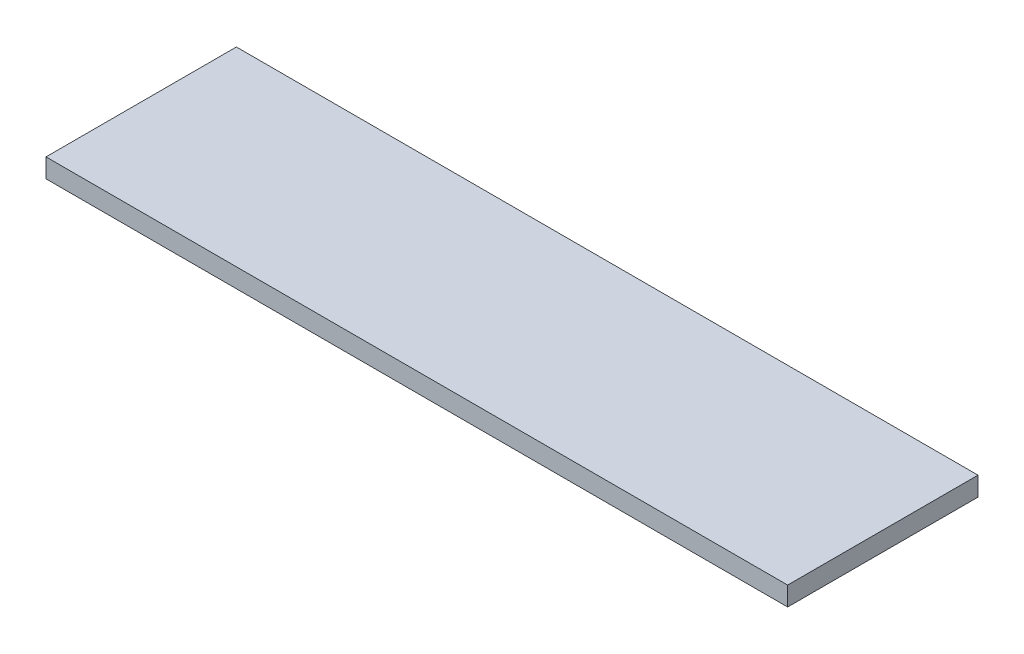
SolidWorks part; units mm, degrees
ref_plane "Front Plane" through (0, 0, 0) normal (0, 0, 1) x (1, 0, 0)
ref_plane "Top Plane" through (0, 0, 0) normal (0, 1, 0) x (1, 0, 0)
ref_plane "Right Plane" through (0, 0, 0) normal (1, 0, 0) x (0, 0, -1)
sketch "Sketch1" plane through (0, 0, 0) normal (0, 1, 0) x (1, 0, 0)
  line L0 (-47.625, 0) -> (47.625, 0) construction
  line L1 (-47.625, 7.9375) -> (47.625, 7.9375)
  line L2 (-47.625, -7.9375) -> (47.625, -7.9375)
  arc A0 (-47.625, 7.9375) -> (-47.625, -7.9375) centre (-47.625, 0) ccw
  arc A1 (47.625, -7.9375) -> (47.625, 7.9375) centre (47.625, 0) ccw
  point P3 (0, 0)
  dimension "D1" = 7.9375
  dimension "D2" = 95.25
extrude "Boss-Extrude1" add sketch "Sketch1" along normal blind 1.5875
sketch "Sketch2" plane through (0, 1.5875, 0) normal (0, 1, 0) x (1, 0, 0)
  line L0 (47.625, 7.9375) -> (-47.625, 7.9375) construction
  line L1 (-30.9245, 7.9375) -> (30.9245, 7.9375)
  line L2 (-30.9245, 7.9375) -> (-30.9245, -7.9375)
  line L3 (-30.9245, -7.9375) -> (30.9245, -7.9375)
  line L4 (30.9245, 7.9375) -> (30.9245, -7.9375)
  line L5 (-47.625, -7.9375) -> (47.625, -7.9375) construction
  line L7 (-71.4249, 20.9127) -> (74.1275, 20.9127)
  line L8 (-71.4249, 20.9127) -> (-71.4249, -19.2397)
  line L9 (-71.4249, -19.2397) -> (74.1275, -19.2397)
  line L10 (74.1275, 20.9127) -> (74.1275, -19.2397)
  dimension "D1" = 61.849
  dimension "D2" = 30.9245
extrude "Cut-Extrude1" cut sketch "Sketch2" against normal up to next
